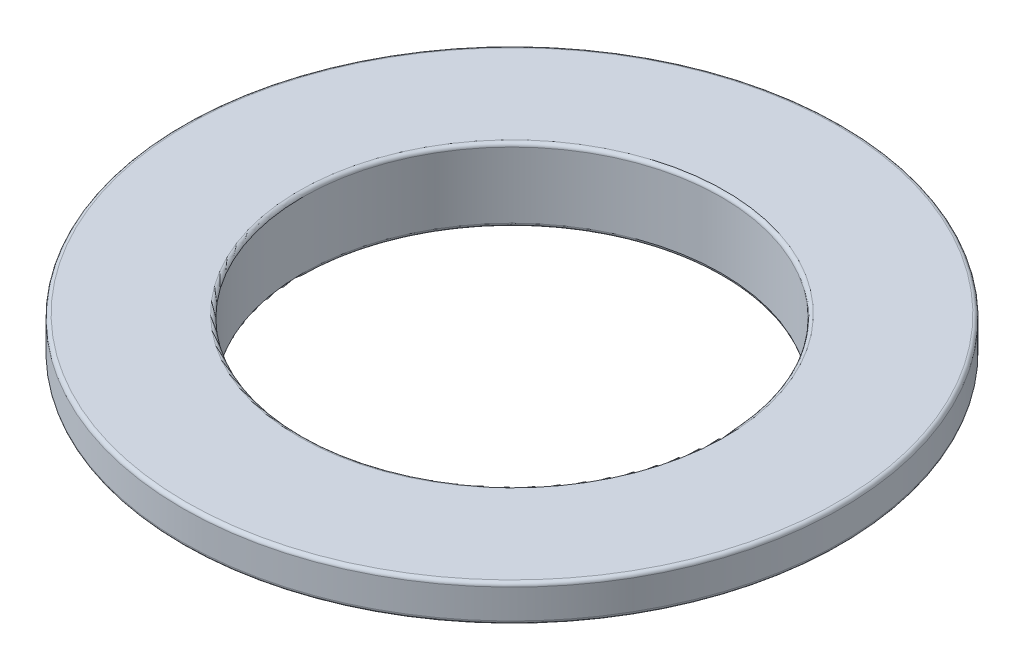
SolidWorks part; units mm, degrees
ref_plane "前视基准面" through (0, 0, 0) normal (0, 0, 1) x (1, 0, 0)
ref_plane "上视基准面" through (0, 0, 0) normal (0, 1, 0) x (1, 0, 0)
ref_plane "右视基准面" through (0, 0, 0) normal (1, 0, 0) x (0, 0, -1)
sketch "Sketch1" plane through (0, 0, 0) normal (0, 0, 1) x (1, 0, 0)
  line L0 (0, 0) -> (16.8, 0) construction
  line L1 (18, 1.833) -> (18, 2.5)
  line L2 (18, 2.5) -> (22.5, 2.5)
  line L3 (22.5, 2.5) -> (22.5, 5)
  line L4 (22.5, 5) -> (14.3, 5)
  line L5 (14.3, 5) -> (14.3, 0)
  line L6 (16.8, 0) -> (14.3, 0)
  line L7 (0, 0) -> (0, 5)
  arc A0 (16.8, 0) -> (18, 1.833) centre (18.8, 0) cw
  dimension "D1" = 2
  dimension "D3" = 18
  dimension "D4" = 2.5
  dimension "D5" = 14.3
  dimension "D6" = 5
  dimension "D7" = 22.5
revolve "Revolve1" add sketch "Sketch1" angle 360 about L7
fillet "Fillet1" radius 0.25 7 edges at (0, 0, -16.8) (0, 1.833, -18) (0, 2.5, -18) (0, 5, -14.3) (0, 0, -14.3) (0, 2.5, -22.5) (0, 5, -22.5)
